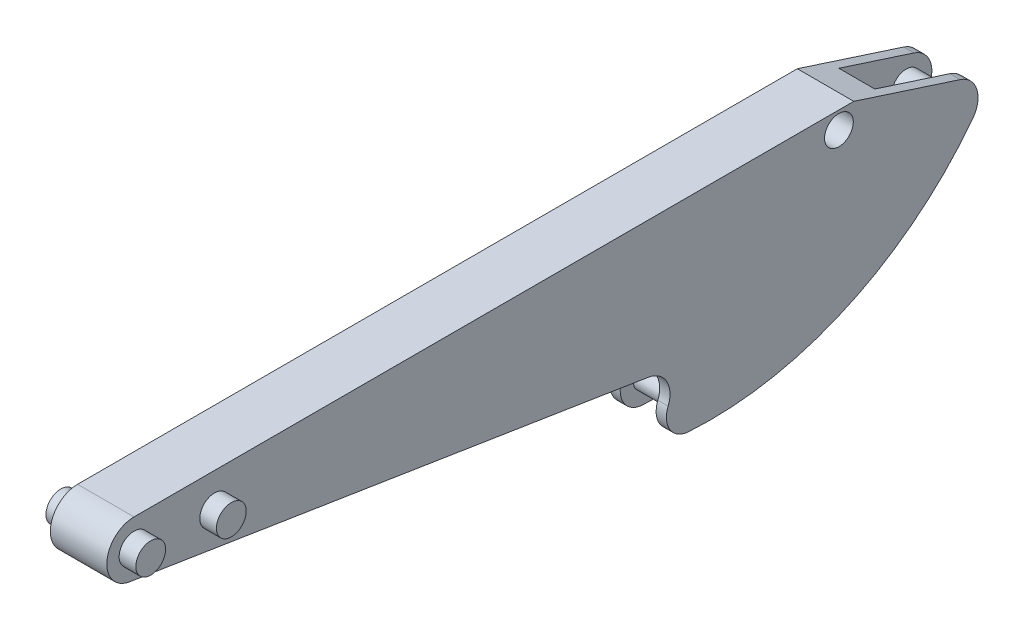
SolidWorks part; units mm, degrees
material "Chrome Stainless Steel"
ref_plane "Plano frontal" through (0, 0, 0) normal (0, 0, 1) x (1, 0, 0)
ref_plane "Plano superior" through (0, 0, 0) normal (0, 1, 0) x (1, 0, 0)
ref_plane "Plano direito" through (0, 0, 0) normal (1, 0, 0) x (0, 0, -1)
sketch "Sketch1" plane through (0, 0, 0) normal (1, 0, 0) x (0, 0, -1)
  line L0 (0, 53) -> (1402, 53)
  line L1 (1402, 53) -> (1609.3721, -14)
  line L2 (-8.291, -52.3475) -> (1001.774, -212.3261)
  line L3 (1594, -61.5783) -> (1800.7113, -61.5783) construction
  line L4 (155.5172, 124.7304) -> (155.5172, -154.4698) construction
  line L5 (54.6449, -14) -> (283.4089, -14) construction
  circle A0 centre (1373, 19) radius 28
  arc A2 (0, 53) -> (-8.291, -52.3475) centre (0, 0) ccw
  arc A3 (1001.774, -212.3261) -> (1040.3313, -280.3917) centre (993.9523, -261.7105) cw
  arc A4 (1040.3313, -280.3917) -> (1079.9119, -343.4746) centre (1083, -297.5783) ccw
  arc A5 (1609.3721, -14) -> (1633.7794, -91.8702) centre (1594, -61.5783) cw
  arc A6 (1633.7794, -91.8702) -> (1079.9119, -343.4746) centre (1123.0114, 297.0771) cw
  dimension "D1" = 53
  dimension "D2" = 14
  dimension "D3" = 33
  dimension "D9" = 50
  dimension "D10" = 46
  dimension "D11" = 50
  dimension "D12" = 642
  dimension "D17" = 1083
  dimension "D4" = 56
  dimension "D5" = 1373
  dimension "D6" = 1402
  dimension "D7" = 221
  dimension "D8" = 9
  dimension "D13" = 236
extrude "Boss-Extrude1" add sketch "Sketch1" along normal mid plane 110 contours A6 A5 L1 L0 A2 L2 A3 A4 A0
sketch "Sketch2" plane through (0, 0, 0) normal (1, 0, 0) x (0, 0, -1)
  line L0 (0, 53) -> (1402, 53)
  line L1 (1249.3917, -251.5449) -> (1462.9003, 33.3237)
  line L2 (1001.774, -212.3261) -> (1249.3917, -251.5449)
  line L3 (1402, 53) -> (1609.3721, -14) construction
  line L4 (1402, 53) -> (1609.3721, -14)
  arc A0 (1633.7794, -91.8702) -> (1609.3721, -14) centre (1594, -61.5783) ccw construction
  arc A1 (1040.3313, -280.3917) -> (1079.9119, -343.4746) centre (1083, -297.5783) ccw construction
  arc A2 (1040.3313, -280.3917) -> (1001.774, -212.3261) centre (993.9523, -261.7105) ccw construction
  arc A3 (1633.7794, -91.8702) -> (1609.3721, -14) centre (1594, -61.5783) ccw
  arc A4 (1040.3313, -280.3917) -> (1079.9119, -343.4746) centre (1083, -297.5783) ccw
  arc A5 (1040.3313, -280.3917) -> (1001.774, -212.3261) centre (993.9523, -261.7105) ccw
  arc A6 (1633.7794, -91.8702) -> (1079.9119, -343.4746) centre (1123.0114, 297.0771) cw
  dimension "D1" = 356
  dimension "D2" = 64
  dimension "D8" = 9
extrude "Cut-Extrude1" cut sketch "Sketch2" against normal mid plane 70 contours A6 A3 L4 L1 L2 A5 A4
sketch "Sketch3" plane through (0, 0, 0) normal (1, 0, 0) x (0, 0, -1)
  circle A0 centre (1594, -61.5783) radius 28
  circle A1 centre (1083, -297.5783) radius 20
  dimension "D1" = 56
  dimension "D2" = 40
extrude "Boss-Extrude2" add sketch "Sketch3" along normal mid plane 70
sketch "Sketch4" plane through (0, 0, 0) normal (1, 0, 0) x (0, 0, -1)
  circle A0 centre (0, 0) radius 29
  circle A1 centre (157, -14) radius 29
  dimension "D1" = 58
  dimension "D2" = 157
  dimension "D3" = 14
extrude "Boss-Extrude3" add sketch "Sketch4" along normal mid plane 175
